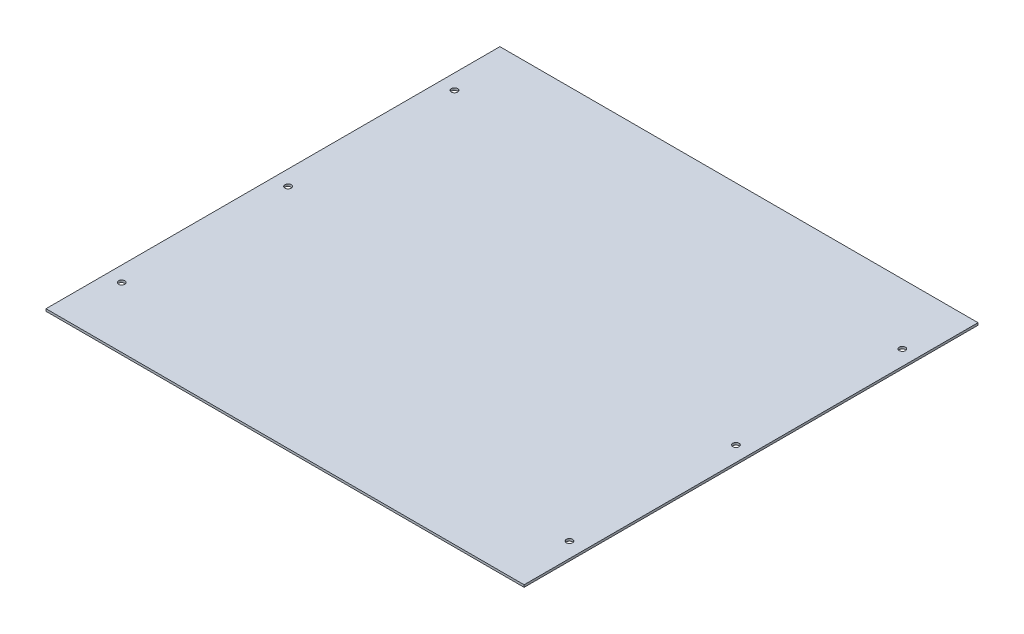
SolidWorks part; units mm, degrees
ref_plane "Front Plane" through (0, 0, 0) normal (0, 0, 1) x (1, 0, 0)
ref_plane "Top Plane" through (0, 0, 0) normal (0, 1, 0) x (1, 0, 0)
ref_plane "Right Plane" through (0, 0, 0) normal (1, 0, 0) x (0, 0, -1)
sketch "Sketch1" plane through (0, 0, 0) normal (0, 1, 0) x (1, 0, 0)
  line L1 (-138, -150) -> (138, -150)
  line L2 (-138, -150) -> (-138, 150)
  line L3 (-138, 150) -> (138, 150)
  line L4 (138, -150) -> (138, 150)
  line L5 (-138, -150) -> (138, 150) construction
  line L6 (-138, 150) -> (138, -150) construction
  point P0 (0, 0)
  dimension "D1" = 276
  dimension "D2" = 300
extrude "Boss-Extrude1" add sketch "Sketch1" along normal blind 1.5 contours L2 L3 L4 L1
sketch "Sketch2" plane through (0, 1.5, 0) normal (0, 1, 0) x (1, 0, 0)
  line L0 (-138, 150) -> (138, 150) construction
  line L1 (-138, -150) -> (-136.5, -150)
  line L2 (-138, -150) -> (-138, 150)
  line L3 (-138, 150) -> (-136.5, 150)
  line L4 (-136.5, -150) -> (-136.5, 150)
  line L6 (138, -150) -> (136.5, -150)
  line L7 (138, -150) -> (138, 150)
  line L8 (138, 150) -> (136.5, 150)
  line L9 (136.5, -150) -> (136.5, 150)
  dimension "D1" = 1.5
  dimension "D2" = 1.5
extrude "Boss-Extrude2" [suppressed] add sketch "Sketch2" along normal blind 20
sketch "Sketch3" plane through (-138, 0, 0) normal (-1, 0, 0) x (0, 0, 1)
  line L0 (-150, 1.5) -> (-150, 0) construction
  line L1 (150, 0) -> (-150, 0)
  line L2 (150, 0) -> (150, 1.5)
  line L3 (150, 1.5) -> (-150, 1.5)
  line L4 (-150, 0) -> (-150, 1.5)
  dimension "D1" = 1.5
extrude "Boss-Extrude3" add sketch "Sketch3" along normal blind 20
sketch "Sketch4" plane through (138, 0, 0) normal (1, 0, 0) x (0, 0, -1)
  line L0 (-150, 1.5) -> (-150, 0) construction
  line L1 (150, 0) -> (-150, 0)
  line L2 (150, 0) -> (150, 1.5)
  line L3 (150, 1.5) -> (-150, 1.5)
  line L4 (-150, 0) -> (-150, 1.5)
  dimension "D1" = 1.5
extrude "Boss-Extrude4" add sketch "Sketch4" along normal blind 20
hole_wizard "Ø4.1 (4.1) Diameter Hole1" positions "Sketch5" profile "Sketch6" hole size "Ø4.1" standard "DIN" end condition up to next
sketch "Sketch5" plane through (0, 0, 0) normal (0, -1, 0) x (-1, 0, 0)
  line L0 (158, 150) -> (-158, 150) construction
  line L1 (-158, -150) -> (-158, 150) construction
  line L2 (158, -150) -> (-158, -150) construction
  line L3 (158, 150) -> (158, -150) construction
  point P0 (-148, 110)
  point P19 (-148, 0)
  point P20 (-148, -110)
  point P21 (148, 0)
  point P22 (148, -110)
  point P23 (148, 110)
  dimension "D1" = 40
  dimension "D2" = 10
  dimension "D5" = 40
  dimension "D6" = 10
  dimension "D3" = 3
  dimension "D4" = 2
sketch "Sketch6" plane through (148, 0, -110) normal (1, 0, 0) x (0, 0, -1)
  line L0 (0, 0) -> (0, 1.5)
  line L1 (0, 1.5) -> (2.05, 1.5)
  line L2 (2.05, 1.5) -> (2.05, 0)
  line L5 (2.05, 0) -> (0, 0)
  line L11 (0, -6.35) -> (0, 107.95) construction
  dimension "Thru Hole Dia." = 4.1
  dimension "Thru Hole Depth" = 1.5
